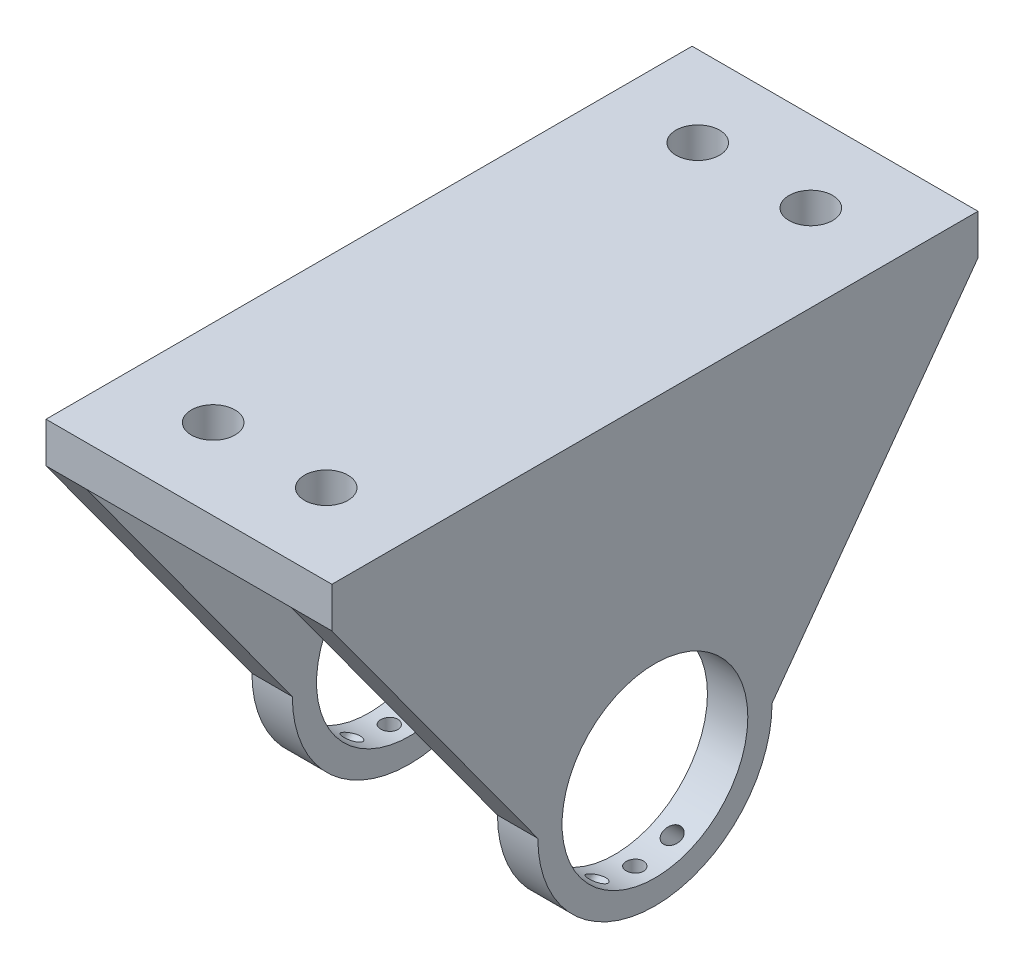
SolidWorks part; units mm, degrees
material "7075-O (SS)"
ref_plane "Front Plane" through (0, 0, 0) normal (0, 0, 1) x (1, 0, 0)
ref_plane "Top Plane" through (0, 0, 0) normal (0, 1, 0) x (1, 0, 0)
ref_plane "Right Plane" through (0, 0, 0) normal (1, 0, 0) x (0, 0, -1)
sketch "Sketch2" plane through (0, 0, 0) normal (0, 1, 0) x (1, 0, 0)
  line L1 (-22.479, 50.8) -> (22.479, 50.8)
  line L2 (-22.479, 50.8) -> (-22.479, -50.8)
  line L3 (-22.479, -50.8) -> (22.479, -50.8)
  line L4 (22.479, 50.8) -> (22.479, -50.8)
  line L5 (-22.479, 50.8) -> (22.479, -50.8) construction
  line L6 (-22.479, -50.8) -> (22.479, 50.8) construction
  point P0 (0, 0)
  dimension "D1" = 44.958
  dimension "D2" = 101.6
extrude "Boss-Extrude1" add sketch "Sketch2" along normal blind 6.35
sketch "Sketch3" plane through (22.479, 0, 0) normal (1, 0, 0) x (0, 0, -1)
  line L0 (-50.8, 6.35) -> (-50.8, 0)
  line L1 (-50.8, 0) -> (-18.415, -44.45)
  line L2 (18.415, -44.45) -> (50.8, 0)
  line L3 (50.8, 0) -> (50.8, 6.35)
  line L4 (50.8, 6.35) -> (-50.8, 6.35)
  line L5 (-50.8, 0) -> (50.8, 0) construction
  arc A0 (-18.415, -44.45) -> (18.415, -44.45) centre (0, -44.45) ccw
  circle A1 centre (0, -44.45) radius 14.605
  dimension "D2" = 18.415
  dimension "D3" = 29.21
  dimension "D1" = 44.45
extrude "Boss-Extrude2" add sketch "Sketch3" against normal blind 6.35
ref_plane "Plane1" through (0, -62.865, 0) normal (0, -1, 0) x (-1, 0, 0)
sketch "Sketch5" plane through (0, -62.865, 0) normal (0, -1, 0) x (-1, 0, 0)
  line L0 (-22.479, 0) -> (-19.304, 0) construction
  line L1 (-22.479, 18.415) -> (-22.479, -18.415) construction
  line L2 (-19.304, 0) -> (-16.129, 0) construction
  line L3 (-16.129, -50.8) -> (-16.129, 50.8) construction
  circle A0 centre (-19.304, 0) radius 1.3526
  dimension "D1" = 2.7051
extrude "Cut-Extrude1" cut sketch "Sketch5" against normal blind 16.256
ref_plane "Plane2" through (0, -9.2036, -9.2036) normal (0, 0.7071, 0.7071) x (1, 0, 0)
ref_plane "Plane3" through (0, -36.1444, -36.1444) normal (0, 0.7071, 0.7071) x (1, 0, 0)
sketch "Sketch6" plane through (0, -36.1444, -36.1444) normal (0, 0.7071, 0.7071) x (1, 0, 0)
  circle A0 centre (19.2831, -36.6741) radius 1.3526
  point P2 (19.2416, -48.6927)
  point P3 (19.2831, -36.6741)
  dimension "D1" = 2.7051
extrude "Cut-Extrude2" cut sketch "Sketch6" along normal blind 9.652
mirror "Mirror1" about plane through (0, 0, 0) normal (0, 0, 1) of "Cut-Extrude2"
mirror "Mirror2" about plane through (0, 0, 0) normal (1, 0, 0) of "Mirror1", "Cut-Extrude2", "Cut-Extrude1", "Boss-Extrude2"
sketch "Sketch7" plane through (0, 0, 0) normal (0, -1, 0) x (1, 0, 0)
  line L1 (-8.89, 38.1) -> (8.89, 38.1) construction
  line L2 (-8.89, 38.1) -> (-8.89, -38.1) construction
  line L3 (-8.89, -38.1) -> (8.89, -38.1) construction
  line L4 (8.89, 38.1) -> (8.89, -38.1) construction
  line L5 (-8.89, 38.1) -> (8.89, -38.1) construction
  line L6 (-8.89, -38.1) -> (8.89, 38.1) construction
  circle A0 centre (-8.89, 38.1) radius 3.429
  circle A1 centre (8.89, 38.1) radius 3.429
  circle A2 centre (8.89, -38.1) radius 3.429
  circle A3 centre (-8.89, -38.1) radius 3.429
  point P0 (0, 0)
  dimension "D3" = 6.858
  dimension "D1" = 76.2
  dimension "D2" = 17.78
extrude "Cut-Extrude3" cut sketch "Sketch7" against normal up to surface (6.35 mm away) up to face at (0, 6.35, 0)
